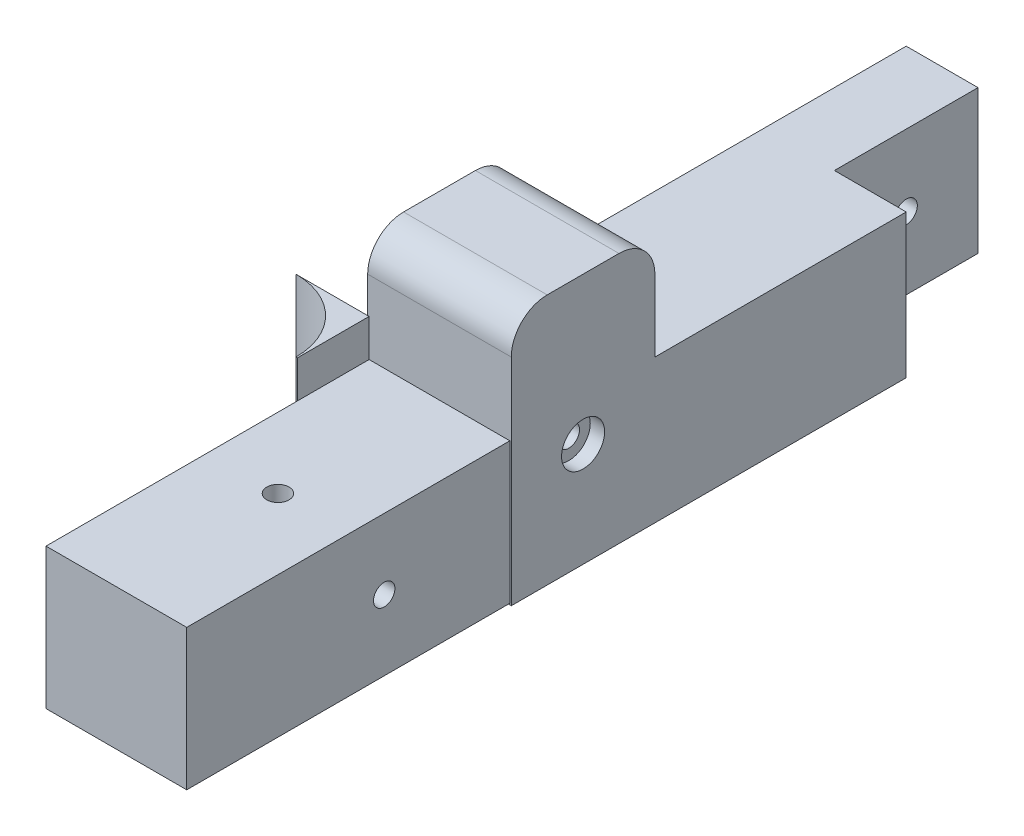
SolidWorks part; units mm, degrees
ref_plane "前视基准面" through (0, 0, 0) normal (0, 0, 1) x (1, 0, 0)
ref_plane "上视基准面" through (0, 0, 0) normal (0, 1, 0) x (1, 0, 0)
ref_plane "右视基准面" through (0, 0, 0) normal (1, 0, 0) x (0, 0, -1)
other "Configuration Table"
sketch "草图1" plane through (0, 0, 0) normal (0, 0, 1) x (1, 0, 0)
  line L1 (0, 0) -> (20, 0)
  line L2 (0, 0) -> (0, 20)
  line L3 (0, 20) -> (20, 20)
  line L4 (20, 0) -> (20, 20)
extrude "凸台-拉伸1" add sketch "草图1" along normal blind 120 contours L2 L1 L4 L3
sketch "草图2" plane through (0, 20, 0) normal (0, 1, 0) x (1, 0, 0)
  line L1 (20, 0) -> (10, 0)
  line L2 (20, 0) -> (20, -20)
  line L3 (20, -20) -> (10, -20)
  line L4 (10, 0) -> (10, -20)
extrude "切除-拉伸1" cut sketch "草图2" against normal blind 120
sketch "草图3" plane through (10, 0, 0) normal (1, 0, 0) x (0, 0, -1)
  line L0 (-20, 20) -> (0, 0)
  circle A0 centre (-10, 10) radius 1.55
extrude "切除-拉伸2" cut sketch "草图3" against normal blind 120 contours L0 A0 | L0 A0
sketch "草图4" plane through (0, 0, 0) normal (-1, 0, 0) x (0, 0, 1)
  circle A0 centre (10, 10) radius 3
extrude "切除-拉伸3" cut sketch "草图4" against normal blind 2
sketch "草图6" plane through (0, 0, 0) normal (-1, 0, 0) x (0, 0, 1)
  line L0 (120, 20) -> (75, 20)
  line L1 (120, 20) -> (0, 20) construction
  line L2 (75, 20) -> (75, 0)
  line L3 (75, 10) -> (92.5, 10)
  circle A0 centre (92.5, 10) radius 1.49
extrude "切除-拉伸4" cut sketch "草图6" against normal blind 20
sketch "草图7" plane through (0, 0, 0) normal (0, -1, 0) x (1, 0, 0)
  line L0 (0, 120) -> (20, 75)
  circle A0 centre (10, 97.5) radius 1.55
extrude "切除-拉伸5" cut sketch "草图7" against normal blind 20 contours L0 A0 | L0 A0
sketch "草图8" plane through (0, 0, 120) normal (0, 0, 1) x (1, 0, 0)
  line L0 (0, 20) -> (0.2, 20)
  line L1 (0, 20) -> (20, 20) construction
  line L2 (0, 20) -> (0, 19.8)
  line L3 (0, 0) -> (0, 20) construction
  line L4 (0, 19.8) -> (20, 19.8)
  line L5 (20, 0) -> (20, 20) construction
  line L6 (0.2, 20) -> (0.2, 19.8)
  line L7 (0.2, 19.8) -> (0.2, 0)
  line L8 (0, 0) -> (20, 0) construction
  line L9 (0.2, 0) -> (0, 0)
  line L10 (0, 0) -> (0, 0.2)
  line L11 (0, 0.2) -> (20, 0.2)
  line L12 (20, 0.2) -> (20, 0)
  line L13 (20, 0) -> (19.8, 0)
  line L14 (19.8, 0) -> (19.8, 20)
  line L15 (19.8, 20) -> (20, 20)
  line L16 (20, 20) -> (20, 0.2)
  line L17 (19.8, 0) -> (0.2, 0)
  line L18 (0.2, 0) -> (19.8, 0)
  line L19 (0, 0.2) -> (0.2, 0.2)
  line L20 (0.2, 0.2) -> (0.2, 0)
  line L21 (0, 0.2) -> (0, 19.8)
  line L22 (0.2, 20) -> (19.8, 20)
  line L23 (19.8, 20) -> (19.8, 19.8)
  line L24 (19.8, 19.8) -> (20, 19.8)
  line M5 (20, 20) -> (0, 20)
  line M6 (0, 20) -> (0, 0)
  line M7 (0, 0) -> (20, 0)
  line M8 (20, 0) -> (20, 20)
extrude "切除-拉伸6" cut sketch "草图8" against normal blind 45 contours L4 L14 L6 M5 | L6 L4 M5 M6 | L11 L7 L4 M6 | L14 L11 L4 M8 | L14 L11 M7 M8 | L14 L11 L7 M7 | L11 L7 M6 M7 | L14 L4 M8 M5
sketch "草图9" plane through (0, 19.8, 0) normal (0, 1, 0) x (1, 0, 0)
  line L1 (0, -75) -> (-10, -75)
  line L2 (0, -85) -> (0.2, -85)
  line L3 (0.2, -75) -> (0.2, -120) construction
  line L4 (0.2, -85) -> (0.2, -75)
  line L5 (0, -75) -> (0.2, -75)
  arc A0 (0, -85) -> (-10, -75) centre (-10, -85) ccw
extrude "凸台-拉伸2" add sketch "草图9" against normal blind 24.8 contours L1 A0 L2 L4 L5
sketch "草图10" plane through (0, 19.8, 0) normal (0, 1, 0) x (1, 0, 0)
  line L0 (-10, -75) -> (0, -75)
  line L3 (0, -85) -> (0.2, -85)
  line L4 (0.2, -85) -> (0.2, -75)
  line L5 (0, -75) -> (19.8, -75) construction
  line L6 (0.2, -75) -> (0, -75)
  arc A0 (0, -85) -> (-10, -75) centre (-10, -85) ccw
  arc A1 (0, -85) -> (-10, -75) centre (-10, -85) ccw construction
extrude "凸台-拉伸3" add sketch "草图10" along normal blind 5.2 contours A0 L3 L4 L6 L0
sketch "草图12" plane through (0, 20, 0) normal (0, 1, 0) x (1, 0, 0)
  line L0 (20, -75) -> (20, -20) construction
  line L1 (0, -75) -> (20, -75)
  line L2 (0, -75) -> (0, -55)
  line L3 (0, -55) -> (20, -55)
  line L4 (20, -75) -> (20, -55)
extrude "凸台-拉伸4" add sketch "草图12" along normal blind 15 contours L2 L1 L4 L3
sketch "草图13" plane through (0, 0, 0) normal (-1, 0, 0) x (0, 0, 1)
  line L0 (55, 20) -> (75, 20)
  line L1 (75, 25) -> (75, 0) construction
  line L2 (65, 20) -> (65, 25)
  line L3 (65, 25) -> (65, 29.5)
  line L4 (65, 29.5) -> (60, 29.5)
  line L5 (65, 29.5) -> (70, 29.5)
  line L6 (60, 29.5) -> (60, 4)
  line L7 (70, 29.5) -> (70, 4)
  line L8 (70, 4) -> (60, 4)
extrude "切除-拉伸7" cut sketch "草图13" against normal blind 15 contours L8 L7 L0 L6 | L4 L6 L0 L2 L3 | L7 L5 L3 L2 L0
sketch "草图14" plane through (0, 0, 0) normal (0, 0, -1) x (-1, 0, 0)
  circle A0 centre (-5, 6) radius 2
extrude "切除-拉伸8" cut sketch "草图14" against normal blind 70 contours A0
sketch "草图15" plane through (15, 0, 0) normal (-1, 0, 0) x (0, 0, 1)
  line L0 (60, 29.5) -> (60, 9.5)
  line L1 (60, 29.5) -> (60, 4) construction
  line L2 (60, 9.5) -> (70, 9.5)
  line L3 (70, 29.5) -> (70, 4) construction
  line L4 (65, 9.5) -> (65, 14.5)
  circle A0 centre (65, 14.5) radius 1.5
extrude "切除-拉伸9" cut sketch "草图15" against normal blind 5
sketch "草图16" plane through (20, 0, 0) normal (1, 0, 0) x (0, 0, -1)
  circle A0 centre (-65, 14.5) radius 3
extrude "切除-拉伸10" cut sketch "草图16" against normal blind 2
sketch "草图17" plane through (0, 0, 0) normal (-1, 0, 0) x (0, 0, 1)
  line L0 (55, 35) -> (60, 35)
  line L1 (75, 35) -> (55, 35) construction
  line L2 (60, 35) -> (60, 30)
  line L3 (75, 35) -> (70, 35)
  line L4 (70, 35) -> (70, 30)
  line L5 (55, 35) -> (55, 20) construction
  line L6 (75, 35) -> (75, 25) construction
  line L7 (55, 30) -> (55, 35)
  line L8 (75, 30) -> (75, 35)
  arc A0 (55, 30) -> (60, 35) centre (60, 30) cw
  arc A1 (75, 30) -> (70, 35) centre (70, 30) ccw
  line M8 (75, 25) -> (75, 35)
  line M9 (75, 35) -> (55, 35)
  line M10 (55, 35) -> (55, 20)
extrude "切除-拉伸11" cut sketch "草图17" against normal blind 20 contours A0 M10 M9 | A1 M8 M9
sketch "草图18" plane through (0, 0, 0) normal (-1, 0, 0) x (0, 0, 1)
  line L1 (70, 4) -> (70.2, 4)
  line L2 (70, 4) -> (70, 29.5)
  line L3 (70, 29.5) -> (70.2, 29.5)
  line L4 (70.2, 4) -> (70.2, 29.5)
  line L5 (60, 4) -> (59.8, 4)
  line L6 (60, 4) -> (60, 29.5)
  line L7 (60, 29.5) -> (59.8, 29.5)
  line L8 (59.8, 4) -> (59.8, 29.5)
  line L9 (59.8, 29.5) -> (70.2, 29.5)
  line L10 (59.8, 29.5) -> (59.8, 29.7)
  line L11 (59.8, 29.7) -> (70.2, 29.7)
  line L12 (70.2, 29.5) -> (70.2, 29.7)
  line M23 (60, 29.5) -> (70, 29.5)
  line M24 (70, 29.5) -> (70, 4)
  line M26 (60, 4) -> (60, 29.5)
extrude "切除-拉伸12" cut sketch "草图18" against normal blind 15 contours L8 L5 L7 M26 | L3 L12 L11 L10 L7 M23 | L1 L4 L3 M24
